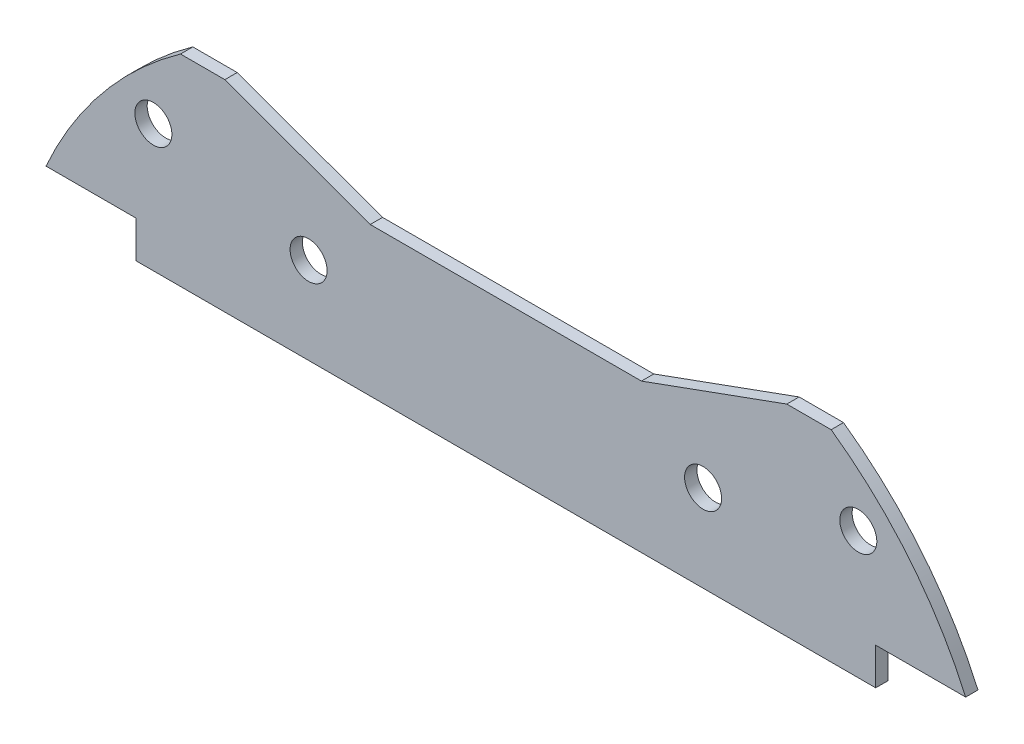
SolidWorks part; units mm, degrees
ref_plane "Front Plane" through (0, 0, 0) normal (0, 0, 1) x (1, 0, 0)
ref_plane "Top Plane" through (0, 0, 0) normal (0, 1, 0) x (1, 0, 0)
ref_plane "Right Plane" through (0, 0, 0) normal (1, 0, 0) x (0, 0, -1)
sketch "Sketch1" plane through (0, 0, 0) normal (0, 0, 1) x (1, 0, 0)
  line L2 (11, 25.5) -> (-11, 25.5)
  line L3 (-11, 25.5) -> (-22.79, 29.7803)
  line L4 (11, 25.5) -> (22.79, 29.7803)
  arc A0 (-22.79, 29.7803) -> (22.79, 29.7803) centre (0, 0) ccw
  arc A1 (-22.79, 29.7803) -> (22.79, 29.7803) centre (0, 0) ccw
  dimension "D2" = 37.5
extrude "Boss-Extrude1" add sketch "Sketch1" along normal blind 3 contours L3 A0 L4 L2
sketch "Sketch2" plane through (0, 0, 3) normal (0, 0, 1) x (1, 0, 0)
  line L0 (0, 0) -> (-25.8, 0) construction
  line L2 (0, 0) -> (0, 15.281) construction
  circle A4 centre (-25.4, 10.4969) radius 1.5
  circle A5 centre (-25.4, -10.4931) radius 1.5
  circle A6 centre (25.4, -10.4931) radius 1.5
  circle A7 centre (25.4, 10.4969) radius 1.5
  point P6 (-25.8, 0)
  dimension "D1" = 25.8
  dimension "D2" = 20.99
extrude "Cut-Extrude3" cut sketch "Sketch2" against normal blind 3
sketch "Sketch3" plane through (0, 0, 3) normal (0, 0, 1) x (1, 0, 0)
  line L1 (-30.76, 21.4493) -> (-30.76, -21.4493)
  line L3 (30.76, 21.4493) -> (30.76, -21.4493)
  arc A0 (-22.79, 29.7803) -> (22.79, 29.7803) centre (0, 0) ccw construction
  arc A1 (-30.76, 21.4493) -> (-30.76, -21.4493) centre (0, 0) ccw
  arc A2 (30.76, 21.4493) -> (30.76, -21.4493) centre (0, 0) cw
  point P10 (-30.76, 0)
extrude "Cut-Extrude4" cut sketch "Sketch3" against normal blind 10
sketch "Sketch4" plane through (0, 0, 3) normal (0, 0, 1) x (1, 0, 0)
  line L0 (-30.76, 21.4493) -> (-30.76, 16.4493) construction
  line L1 (-30.76, -21.4493) -> (-30.76, 21.4493) construction
  line L2 (30.76, 21.4493) -> (30.76, 16.4493) construction
  line L3 (30.76, 21.4493) -> (30.76, -21.4493) construction
  line L4 (-30.76, -21.4493) -> (-30.76, -16.4493) construction
  line L5 (30.76, -21.4493) -> (30.76, -16.4493) construction
  line L6 (-30.76, -16.4493) -> (-33.6997, -16.4493)
  line L7 (-30.76, 16.4493) -> (-33.6997, 16.4493)
  line L8 (30.76, 16.4493) -> (33.6997, 16.4493)
  line L9 (30.76, -16.4493) -> (33.6997, -16.4493)
  line L10 (30.76, -21.4493) -> (30.76, -16.4493)
  line L11 (30.76, 21.4493) -> (30.76, 16.4493)
  line L12 (-30.76, 16.4493) -> (-30.76, 21.4493)
  line L13 (-30.76, -21.4493) -> (-30.76, -16.4493)
  arc A0 (-33.6997, -16.4493) -> (33.6997, -16.4493) centre (0, 0) ccw
  arc A1 (-30.76, 21.4493) -> (-33.6997, 16.4493) centre (0, 0) ccw
  arc A2 (33.6997, 16.4493) -> (30.76, 21.4493) centre (0, 0) ccw
  line M2 (30.76, -21.4493) -> (30.76, 21.4493)
  line M8 (-30.76, 21.4493) -> (-30.76, -21.4493)
  dimension "D1" = 5
  dimension "D2" = 5
extrude "Boss-Extrude2" add sketch "Sketch4" against normal blind 3 contours L6 A0 M8 | A1 L7 M8 | L8 A2 M2 | A0 L9 M2
sketch "Sketch5" plane through (0, 0, 3) normal (0, 0, 1) x (1, 0, 0)
  line L0 (-30.76, 16.4493) -> (-30.2, 16.4493) construction
  line L1 (-30.76, -16.4493) -> (-30.2, -16.4493) construction
  line L2 (0, 0) -> (0, -3.3934) construction
  line L3 (-30.2, -16.4493) -> (-30.76, -16.4493)
  line L4 (-30.2, -16.4493) -> (-30.2, 16.4493)
  line L5 (-30.2, 16.4493) -> (-30.76, 16.4493)
  line L6 (-30.76, -16.4493) -> (-30.76, 16.4493)
  line L7 (30.76, -16.4493) -> (30.2, -16.4493) construction
  line L8 (30.76, 16.4493) -> (30.2, 16.4493) construction
  line L9 (30.76, -16.4493) -> (30.76, 16.4493)
  line L10 (30.2, 16.4493) -> (30.76, 16.4493)
  line L11 (30.2, -16.4493) -> (30.2, 16.4493)
  line L12 (30.2, -16.4493) -> (30.76, -16.4493)
  dimension "D2" = 0.56
extrude "Cut-Extrude5" cut sketch "Sketch5" against normal blind 3
sketch "Sketch6" plane through (0, 0, 3) normal (0, 0, 1) x (1, 0, 0)
  line L1 (-30.2, 16.4493) -> (-30, 16.4493)
  line L2 (-30.2, 16.4493) -> (-30.2, -16.4493)
  line L3 (-30.2, -16.4493) -> (-30, -16.4493)
  line L4 (-30, 16.4493) -> (-30, -16.4493)
  line L5 (30, 16.4493) -> (30, -16.4493)
  line L6 (30.2, -16.4493) -> (30, -16.4493)
  line L7 (30.2, 16.4493) -> (30.2, -16.4493)
  line L8 (30.2, 16.4493) -> (30, 16.4493)
  dimension "D1" = 0.2
extrude "Cut-Extrude6" cut sketch "Sketch6" against normal blind 3
sketch "Sketch7" plane through (0, 0, 3) normal (0, 0, 1) x (1, 0, 0)
  line L0 (0, -37.5) -> (0, -5.6) construction
  line L1 (0, -21.55) -> (-21.15, -21.55) construction
  line L2 (-21.15, -21.55) -> (-19.15, -21.55) construction
  arc A0 (-33.6997, -16.4493) -> (33.6997, -16.4493) centre (0, 0) ccw construction
  circle A1 centre (-19.15, -21.55) radius 2
  circle A2 centre (19.15, -21.55) radius 2
  dimension "D1" = 31.9
  dimension "D2" = 21.15
  dimension "D3" = 2
extrude "Cut-Extrude8" cut sketch "Sketch7" against normal blind 3 contours A1 | A2
sketch "Sketch8" plane through (0, 0, 3) normal (0, 0, 1) x (1, 0, 0)
  line L2 (-33.6997, 16.4493) -> (-37.2997, 16.4493)
  line L3 (33.6997, 16.4493) -> (37.2997, 16.4493)
  line L4 (-22.79, 29.7803) -> (-26.39, 29.7803)
  line L5 (22.79, 29.7803) -> (26.39, 29.7803)
  line L6 (0, 0) -> (0, 7.7073) construction
  arc A0 (-37.2997, 16.4493) -> (-26.39, 29.7803) centre (-7.6125, 3.2837) cw
  arc A1 (37.2997, 16.4493) -> (26.39, 29.7803) centre (7.6125, 3.2837) ccw
  arc A7 (-33.6997, 16.4493) -> (-22.79, 29.7803) centre (0, 0) cw
  arc A8 (22.79, 29.7803) -> (33.6997, 16.4493) centre (0, 0) cw
  dimension "D4" = 3.6
extrude "Boss-Extrude3" add sketch "Sketch8" against normal blind 3
sketch "Sketch9" plane through (0, 0, 3) normal (0, 0, 1) x (1, 0, 0)
  line L0 (0, 0) -> (0, 9.4958) construction
  line L1 (0, -37.5) -> (0, -37.2) construction
  line L2 (4.7339, -37.2) -> (-4.7339, -37.2)
  arc A0 (-33.6997, -16.4493) -> (33.6997, -16.4493) centre (0, 0) ccw construction
  arc A1 (-4.7339, -37.2) -> (4.7339, -37.2) centre (0, 0) ccw
  point P15 (0, -37.2)
  dimension "D1" = 0.3
extrude "Cut-Extrude9" cut sketch "Sketch9" against normal blind 3
sketch "Sketch10" plane through (0, 0, 3) normal (0, 0, 1) x (1, 0, 0)
  line L0 (-33.6997, -16.4493) -> (-37.2997, -16.4493)
  line L1 (-33.6997, -16.4493) -> (-37.2997, -16.4493) construction
  line L2 (0, 0) -> (0, 6.5031) construction
  line L3 (33.6997, -16.4493) -> (37.2997, -16.4493)
  line L4 (-4.7339, -37.2) -> (4.7339, -37.2)
  arc A0 (-37.2997, -16.4493) -> (37.2997, -16.4493) centre (0, 6.1588) ccw
  arc A1 (-33.6997, -16.4493) -> (-4.7339, -37.2) centre (0, 0) ccw
  arc A2 (33.6997, -16.4493) -> (4.7339, -37.2) centre (0, 0) cw
extrude "Boss-Extrude5" add sketch "Sketch10" against normal blind 3
sketch "Sketch11" plane through (0, 0, 3) normal (0, 0, 1) x (1, 0, 0)
  line L0 (-30, 16.4493) -> (-30, 13.4493)
  line L1 (-30, -16.4493) -> (-30, 16.4493) construction
  line L2 (-30, 13.4493) -> (30, 13.4493)
  line L3 (30, 16.4493) -> (30, -16.4493) construction
  line L4 (30, 13.4493) -> (30, 16.4493)
  line L5 (30, 16.4493) -> (37.2997, 16.4493)
  line L6 (-30, 16.4493) -> (-37.2997, 16.4493)
  line L7 (-26.39, 29.7803) -> (-22.79, 29.7803)
  line L8 (-22.79, 29.7803) -> (-11, 25.5)
  line L9 (-11, 25.5) -> (11, 25.5)
  line L10 (11, 25.5) -> (22.79, 29.7803)
  line L11 (22.79, 29.7803) -> (26.39, 29.7803)
  arc A0 (-37.2997, 16.4493) -> (-26.39, 29.7803) centre (-7.6125, 3.2837) cw
  arc A1 (37.2997, 16.4493) -> (26.39, 29.7803) centre (7.6125, 3.2837) ccw
  dimension "D1" = 3
extrude "Cut-Extrude10" cut sketch "Sketch11" against normal blind 2
sketch "Sketch12" plane through (0, 0, 3) normal (0, 0, 1) x (1, 0, 0)
  line L0 (-30, 13.4493) -> (-30, -16.4493)
  line L1 (-30, -16.4493) -> (-37.2997, -16.4493)
  line L2 (-30, 13.4493) -> (30, 13.4493)
  line L3 (30, 13.4493) -> (30, -16.4493)
  line L4 (30, -16.4493) -> (37.2997, -16.4493)
  arc A0 (-37.2997, -16.4493) -> (37.2997, -16.4493) centre (0, 6.1588) ccw
extrude "Cut-Extrude11" cut sketch "Sketch12" against normal blind 3
sketch "Sketch13" plane through (0, 0, 1) normal (0, 0, 1) x (1, 0, 0)
  line L0 (-24.59, 29.7803) -> (-24.59, 23.7803) construction
  line L1 (-22.79, 29.7803) -> (-26.39, 29.7803) construction
  line L2 (-24.59, 23.7803) -> (-28.59, 23.7803) construction
  circle A0 centre (-28.59, 23.7803) radius 1.5
  circle A1 centre (28.59, 23.7803) radius 1.5
  dimension "D3" = 3
  dimension "D1" = 6
  dimension "D2" = 4
extrude "Cut-Extrude12" cut sketch "Sketch13" against normal blind 1
sketch "Sketch15" plane through (0, 0, 0) normal (0, 0, -1) x (-1, 0, 0)
  line L0 (-11, 25.5) -> (-16, 25.5) construction
  line L1 (-16, 25.5) -> (-16, 20.5) construction
  line L2 (0, 25.5) -> (0, 22) construction
  line L3 (-11, 25.5) -> (11, 25.5) construction
  circle A0 centre (-16, 20.5) radius 1.5
  circle A1 centre (16, 20.5) radius 1.5
  dimension "D1" = 5
  dimension "D2" = 5
extrude "Cut-Extrude13" cut sketch "Sketch15" against normal blind 10
